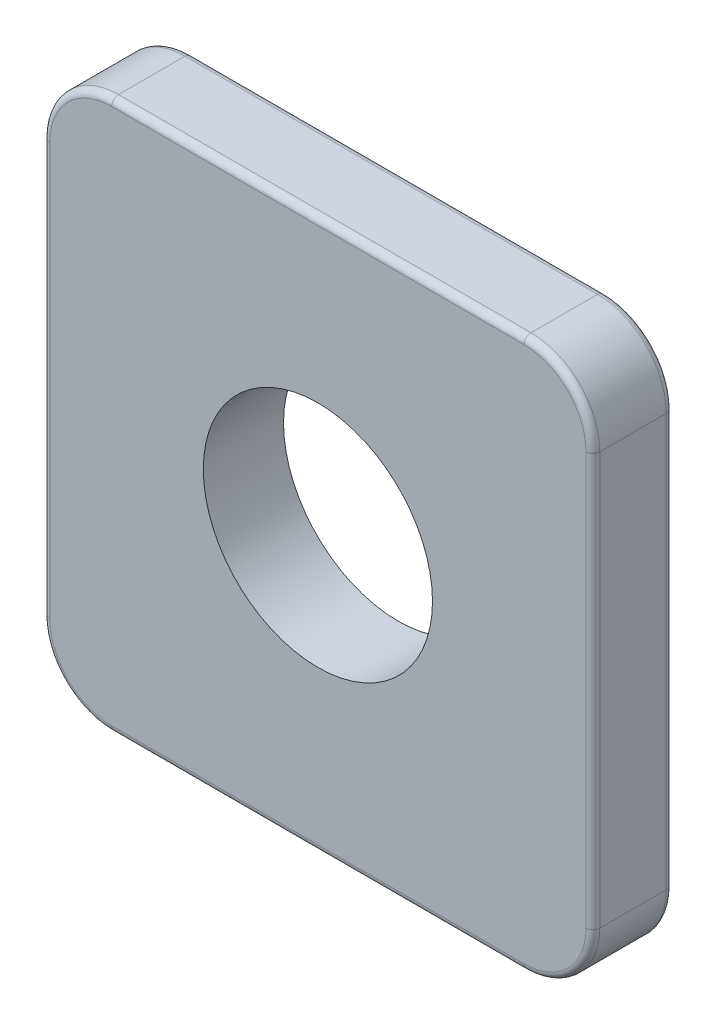
SolidWorks part; units mm, degrees
ref_plane "Front Plane" through (0, 0, 0) normal (0, 0, 1) x (1, 0, 0)
ref_plane "Top Plane" through (0, 0, 0) normal (0, 1, 0) x (1, 0, 0)
ref_plane "Right Plane" through (0, 0, 0) normal (1, 0, 0) x (0, 0, -1)
sketch "Sketch1" plane through (0, 0, 0) normal (0, 0, 1) x (1, 0, 0)
  line L1 (9, -12) -> (-9, -12)
  line L2 (12, -9) -> (12, 9)
  line L3 (9, 12) -> (-9, 12)
  line L4 (-12, -9) -> (-12, 9)
  line L5 (12, -12) -> (-12, 12) construction
  line L6 (12, 12) -> (-12, -12) construction
  arc A0 (9, -12) -> (12, -9) centre (9, -9) ccw
  arc A1 (-9, -12) -> (-12, -9) centre (-9, -9) cw
  arc A2 (12, 9) -> (9, 12) centre (9, 9) ccw
  arc A3 (-9, 12) -> (-12, 9) centre (-9, 9) ccw
  circle A4 centre (0, 0) radius 5
  point P0 (0, 0)
  dimension "D3" = 3
  dimension "D4" = 10
  dimension "D1" = 24
  dimension "D2" = 24
extrude "Boss-Extrude1" add sketch "Sketch1" along normal mid plane 3.5
fillet "Fillet1" radius 0.3 16 edges at (11.1213, -11.1213, -1.75) (0, -12, -1.75) (-11.1213, -11.1213, -1.75) (-12, 0, -1.75) (-11.1213, 11.1213, -1.75) (0, 12, -1.75) (11.1213, 11.1213, -1.75) (11.1213, -11.1213, 1.75) (0, -12, 1.75) (-11.1213, -11.1213, 1.75) (-12, 0, 1.75) (-11.1213, 11.1213, 1.75) (0, 12, 1.75) (11.1213, 11.1213, 1.75) (12, 0, -1.75) (12, 0, 1.75)
